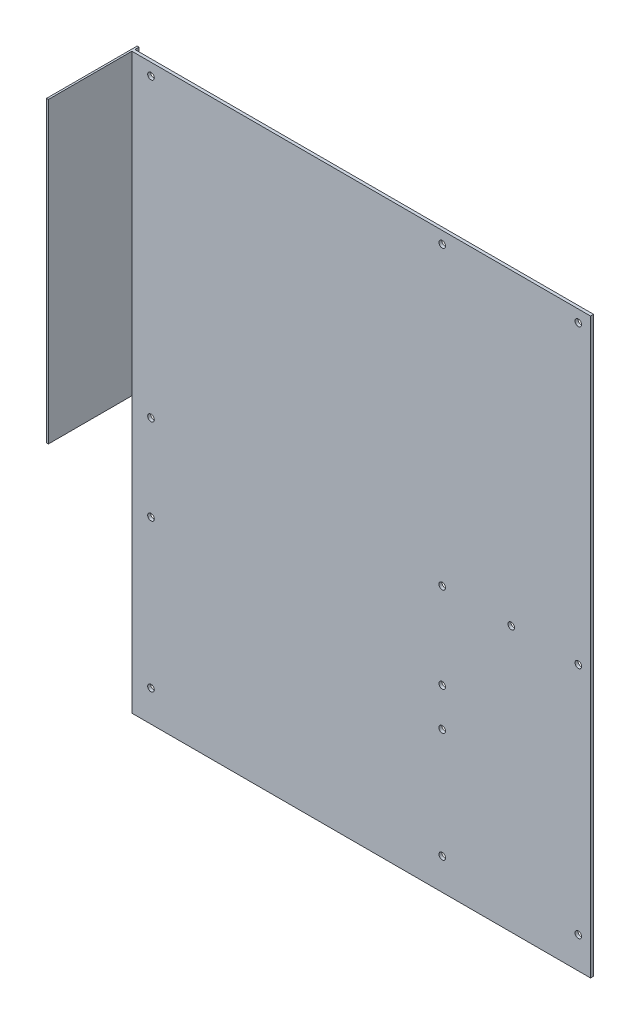
SolidWorks part; units mm, degrees
ref_plane "前视基准面" through (0, 0, 0) normal (0, 0, 1) x (1, 0, 0)
ref_plane "上视基准面" through (0, 0, 0) normal (0, 1, 0) x (1, 0, 0)
ref_plane "右视基准面" through (0, 0, 0) normal (1, 0, 0) x (0, 0, -1)
other "Configuration Table"
sketch "草图1" plane through (0, 0, 0) normal (0, 0, 1) x (1, 0, 0)
  line L0 (0, 0) -> (244, 0)
  line L1 (244, 0) -> (244, 305)
  line L2 (244, 305) -> (0, 305)
  line L3 (0, 305) -> (0, 0)
  dimension "D1" = 244
  dimension "D2" = 305
extrude "凸台-拉伸1" add sketch "草图1" along normal blind 1.6
sketch "草图2" plane through (0, 0, 1.6) normal (0, 0, 1) x (1, 0, 0)
  line L0 (0, 305) -> (0, 0) construction
  line L1 (0, 0) -> (244, 0) construction
  circle A0 centre (10.16, 16.69) radius 1.75
  circle A1 centre (165.1, 16.69) radius 1.75
  circle A2 centre (237.49, 16.69) radius 1.75
  circle A3 centre (165.1, 75.11) radius 1.75
  circle A4 centre (10.16, 95.43) radius 1.75
  circle A5 centre (165.1, 95.43) radius 1.75
  circle A6 centre (10.16, 141.15) radius 1.75
  circle A7 centre (165.1, 141.15) radius 1.75
  circle A8 centre (237.49, 141.15) radius 1.75
  circle A9 centre (10.16, 298.63) radius 1.75
  circle A10 centre (165.1, 298.63) radius 1.75
  circle A11 centre (237.49, 298.63) radius 1.75
  circle A12 centre (201.816, 141.15) radius 1.75
  dimension "D1" = 3.5
  dimension "D4" = 3.5
  dimension "D6" = 3.5
  dimension "D8" = 3.5
  dimension "D11" = 3.5
  dimension "D12" = 3.5
  dimension "D14" = 3.5
  dimension "D15" = 3.5
  dimension "D16" = 3.5
  dimension "D18" = 3.5
  dimension "D19" = 3.5
  dimension "D20" = 3.5
  dimension "D21" = 3.5
  dimension "D2" = 10.16
  dimension "D3" = 16.69
  dimension "D5" = 154.94
  dimension "D7" = 72.39
  dimension "D9" = 58.42
  dimension "D10" = 20.32
  dimension "D13" = 45.72
  dimension "D17" = 157.48
  dimension "D22" = 36.716
extrude "切除-拉伸1" cut sketch "草图2" against normal through all
sketch "草图3" plane through (0, 0, 1.6) normal (0, 0, 1) x (1, 0, 0)
  line L0 (0, 305) -> (-1, 305)
  line L1 (-1, 305) -> (-1, 146.25)
  line L2 (-1, 146.25) -> (0, 146.25)
  line L3 (0, 305) -> (0, 0) construction
  line L8 (0, 305) -> (0, 0)
  line L9 (0, 0) -> (244, 0)
  line L10 (244, 0) -> (244, 305)
  line L11 (244, 305) -> (0, 305)
  line L12 (0, 305) -> (0, 146.25)
  dimension "D1" = 158.75
  dimension "D2" = 1
  dimension "D3" = 0
extrude "凸台-拉伸2" add sketch "草图3" along normal blind 44.45 and the other way blind 3.81
